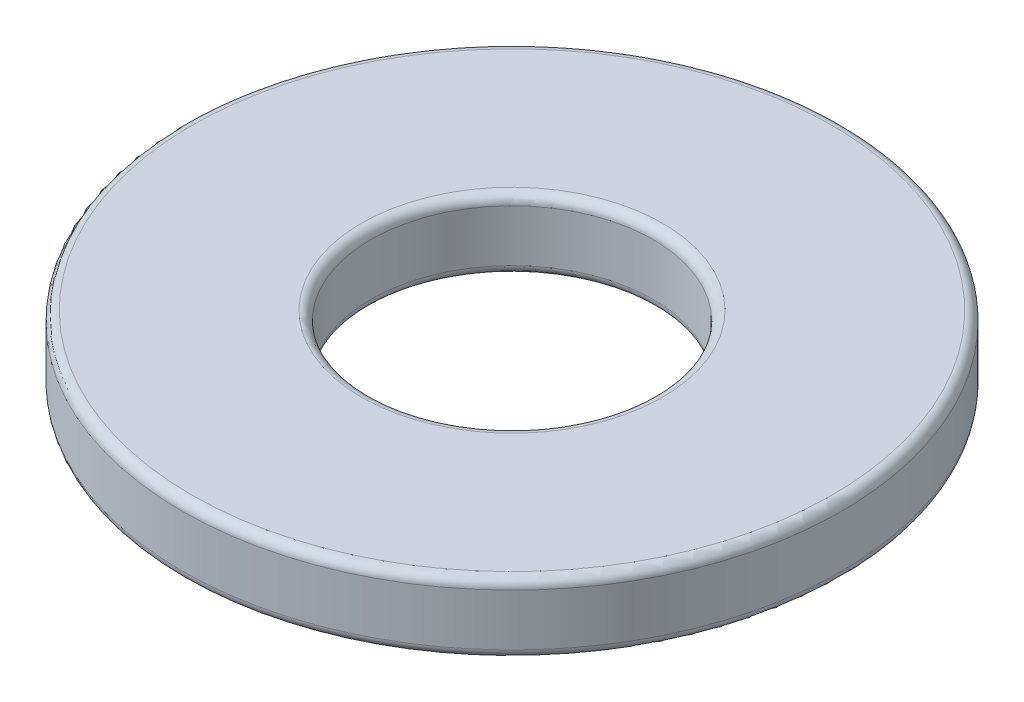
SolidWorks part; units mm, degrees
ref_plane "Front Plane" through (0, 0, 0) normal (0, 0, 1) x (1, 0, 0)
ref_plane "Top Plane" through (0, 0, 0) normal (0, 1, 0) x (1, 0, 0)
ref_plane "Right Plane" through (0, 0, 0) normal (1, 0, 0) x (0, 0, -1)
sketch "Sketch1" plane through (0, 0, 0) normal (0, 1, 0) x (1, 0, 0)
  circle A0 centre (0, 0) radius 3.5
  circle A1 centre (0, 0) radius 1.5
  dimension "D1" = 3
  dimension "D2" = 7
extrude "Boss-Extrude1" add sketch "Sketch1" along normal blind 0.75
fillet "Fillet1" radius 0.1 4 edges at (0, 0, 3.5) (0, 0.75, 3.5) (0, 0, 1.5) (0, 0.75, 1.5)
